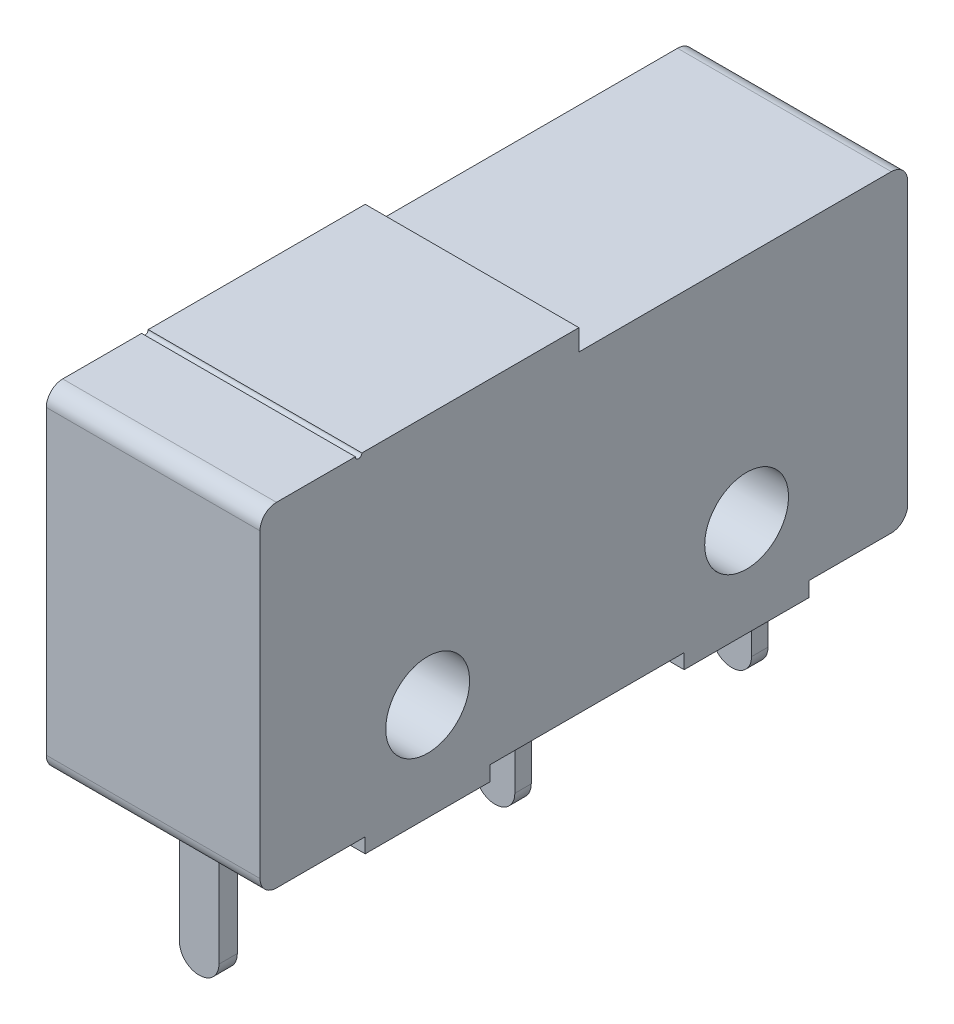
SolidWorks part; units mm, degrees
ref_plane "Front Plane" through (0, 0, 0) normal (0, 0, 1) x (1, 0, 0)
ref_plane "Top Plane" through (0, 0, 0) normal (0, 1, 0) x (1, 0, 0)
ref_plane "Right Plane" through (0, 0, 0) normal (1, 0, 0) x (0, 0, -1)
sketch "Sketch1" plane through (0, 0, 0) normal (1, 0, 0) x (0, 0, -1)
  line L0 (-37.3731, 0) -> (-34.6731, 0)
  line L1 (-37.8731, 0.5) -> (-37.8731, 9.66)
  line L2 (-37.3731, 10.16) -> (-28.1731, 10.16)
  line L3 (-28.1731, 10.16) -> (-28.1731, 9.52)
  line L4 (-28.1731, 9.52) -> (-18.6731, 9.52)
  line L5 (-18.1731, 9.02) -> (-18.1731, 0.5)
  line L6 (-34.6731, 0) -> (-34.6731, -0.45)
  line L7 (-34.6731, -0.45) -> (-30.8731, -0.45)
  line L8 (-30.8731, -0.45) -> (-30.8731, 0)
  line L9 (-30.8731, 0) -> (-24.9731, 0)
  line L10 (-24.9731, 0) -> (-24.9731, -0.45)
  line L11 (-24.9731, -0.45) -> (-21.1731, -0.45)
  line L12 (-21.1731, -0.45) -> (-21.1731, 0)
  line L13 (-21.1731, 0) -> (-18.6731, 0)
  line L14 (-32.7731, -0.45) -> (-32.7731, 2.9938) construction
  line L15 (-23.0731, -0.45) -> (-23.0731, 2.9938) construction
  arc A0 (-18.6731, 9.52) -> (-18.1731, 9.02) centre (-18.6731, 9.02) cw
  arc A1 (-18.6731, 0) -> (-18.1731, 0.5) centre (-18.6731, 0.5) ccw
  arc A2 (-37.3731, 0) -> (-37.8731, 0.5) centre (-37.3731, 0.5) cw
  arc A3 (-37.8731, 9.66) -> (-37.3731, 10.16) centre (-37.3731, 9.66) cw
  circle A4 centre (-32.7731, 2.525) radius 1.275
  circle A5 centre (-23.0731, 2.525) radius 1.275
  point P18 (-23.0731, -0.45)
  point P19 (-18.1731, 9.52)
  point P22 (-18.1731, 0)
  point P25 (-37.8731, 0)
  point P28 (-37.8731, 10.16)
  point P29 (-32.7731, -0.45)
  point P38 (-32.7731, 1.25)
  point P39 (-23.0731, 1.25)
  dimension "D11" = 0.5
  dimension "D12" = 2.55
  dimension "D13" = 2.55
  dimension "D1" = 9.52
  dimension "D2" = 10.16
  dimension "D3" = 3.8
  dimension "D4" = 3.8
  dimension "D5" = 0.45
  dimension "D6" = 0.45
  dimension "D7" = 19.7
  dimension "D8" = 3.2
  dimension "D9" = 9.7
  dimension "D10" = 5.9
  dimension "D14" = 1.7
  dimension "D15" = 1.7
extrude "Boss-Extrude1" add sketch "Sketch1" along normal blind 6.5
sketch "Sketch2" plane through (0, 10.16, 0) normal (0, 1, 0) x (1, 0, 0)
  line L0 (6.5, -28.1731) -> (6.5, -37.3731) construction
  line L1 (5.4, -31.6731) -> (1.87, -31.6731)
  line L2 (5.4, -31.6731) -> (5.4, -29.7131)
  line L3 (5.4, -29.7131) -> (1.87, -29.7131)
  line L4 (1.87, -31.6731) -> (1.87, -29.7131)
  line L5 (5.4, -31.6731) -> (1.87, -29.7131) construction
  line L6 (5.4, -29.7131) -> (1.87, -31.6731) construction
  line L7 (6.5, -37.8731) -> (0, -37.8731) construction
  point P0 (3.635, -30.6931)
  dimension "D1" = 1.96
  dimension "D2" = 3.53
  dimension "D3" = 1.1
  dimension "D4" = 6.2
sketch "Sketch3" plane through (0, 0, 0) normal (0, -1, 0) x (-1, 0, 0)
  line L0 (-3.25, -37.3731) -> (-3.25, -18.1731) construction
  line L1 (-6.5, -37.3731) -> (0, -37.3731) construction
  line L2 (-6.5, -18.1731) -> (0, -18.1731) construction
  line L3 (-6.5, -37.8731) -> (0, -37.8731) construction
  line L4 (-1.65, -36.4731) -> (-4.85, -36.4731)
  line L5 (-1.65, -36.4731) -> (-1.65, -35.9131)
  line L6 (-1.65, -35.9131) -> (-4.85, -35.9131)
  line L7 (-4.85, -36.4731) -> (-4.85, -35.9131)
  line L8 (-1.65, -36.4731) -> (-4.85, -35.9131) construction
  line L9 (-1.65, -35.9131) -> (-4.85, -36.4731) construction
  line L10 (-1.65, -26.9731) -> (-4.85, -26.9731)
  line L11 (-1.65, -26.9731) -> (-1.65, -27.4731)
  line L12 (-1.65, -27.4731) -> (-4.85, -27.4731)
  line L13 (-4.85, -26.9731) -> (-4.85, -27.4731)
  line L14 (-1.65, -26.9731) -> (-4.85, -27.4731) construction
  line L15 (-1.65, -27.4731) -> (-4.85, -26.9731) construction
  line L16 (-1.65, -19.7731) -> (-4.85, -19.7731)
  line L17 (-1.65, -19.7731) -> (-1.65, -20.2731)
  line L18 (-1.65, -20.2731) -> (-4.85, -20.2731)
  line L19 (-4.85, -19.7731) -> (-4.85, -20.2731)
  line L20 (-1.65, -19.7731) -> (-4.85, -20.2731) construction
  line L21 (-1.65, -20.2731) -> (-4.85, -19.7731) construction
  point P6 (-3.25, -36.1931)
  point P11 (-3.25, -27.2231)
  point P16 (-3.25, -20.0231)
  dimension "D1" = 3.2
  dimension "D2" = 0.56
  dimension "D3" = 3.2
  dimension "D4" = 0.5
  dimension "D5" = 3.2
  dimension "D6" = 0.5
  dimension "D7" = 1.6
  dimension "D8" = 1.4
  dimension "D9" = 6.7
extrude "Boss-Extrude3" add sketch "Sketch3" along normal blind 0.9
sketch "Sketch4" plane through (0, -0.9, 0) normal (0, -1, 0) x (-1, 0, 0)
  line L0 (-3.25, -36.4731) -> (-3.25, -19.7731) construction
  line L1 (-4.85, -36.4731) -> (-1.65, -36.4731) construction
  line L2 (-1.65, -19.7731) -> (-4.85, -19.7731) construction
  line L3 (-4.85, -36.4731) -> (-1.65, -36.4731) construction
  line L4 (-2.65, -36.4731) -> (-3.85, -36.4731)
  line L5 (-2.65, -36.4731) -> (-2.65, -35.9131)
  line L6 (-2.65, -35.9131) -> (-3.85, -35.9131)
  line L7 (-3.85, -36.4731) -> (-3.85, -35.9131)
  line L8 (-2.65, -36.4731) -> (-3.85, -35.9131) construction
  line L9 (-2.65, -35.9131) -> (-3.85, -36.4731) construction
  line L10 (-1.65, -35.9131) -> (-4.85, -35.9131) construction
  line L11 (-4.85, -27.4731) -> (-1.65, -27.4731) construction
  line L12 (-3.85, -26.9731) -> (-2.65, -26.9731)
  line L13 (-3.85, -26.9731) -> (-3.85, -27.4731)
  line L14 (-3.85, -27.4731) -> (-2.65, -27.4731)
  line L15 (-2.65, -26.9731) -> (-2.65, -27.4731)
  line L16 (-3.85, -26.9731) -> (-2.65, -27.4731) construction
  line L17 (-3.85, -27.4731) -> (-2.65, -26.9731) construction
  line L18 (-1.65, -26.9731) -> (-4.85, -26.9731) construction
  line L19 (-4.85, -20.2731) -> (-1.65, -20.2731) construction
  line L20 (-3.85, -19.7731) -> (-2.65, -19.7731)
  line L21 (-3.85, -19.7731) -> (-3.85, -20.2731)
  line L22 (-3.85, -20.2731) -> (-2.65, -20.2731)
  line L23 (-2.65, -19.7731) -> (-2.65, -20.2731)
  line L24 (-3.85, -19.7731) -> (-2.65, -20.2731) construction
  line L25 (-3.85, -20.2731) -> (-2.65, -19.7731) construction
  line L26 (-1.65, -19.7731) -> (-4.85, -19.7731) construction
  point P6 (-3.25, -36.1931)
  point P15 (-3.25, -27.2231)
  point P24 (-3.25, -20.0231)
  dimension "D1" = 1.2
  dimension "D2" = 1.2
  dimension "D3" = 1.2
extrude "Boss-Extrude4" add sketch "Sketch4" along normal blind 3.47
fillet "Fillet2" radius 0.59 6 edges at (2.65, -4.37, 36.1931) (3.85, -4.37, 36.1931) (2.65, -4.37, 27.2231) (3.85, -4.37, 27.2231) (3.85, -4.37, 20.0231) (2.65, -4.37, 20.0231)
sketch "Esboço1" plane through (0, 0, 0) normal (-1, 0, 0) x (0, 0, 1)
  line L0 (37.8731, 9.66) -> (37.8731, 10.16) construction
  line L1 (37.8731, 10.16) -> (34.8731, 10.16) construction
  line L2 (28.1731, 10.16) -> (37.3731, 10.16) construction
  circle A0 centre (34.8731, 10.16) radius 0.1
extrude "Corte-extrusão1" cut sketch "Esboço1" against normal through all
